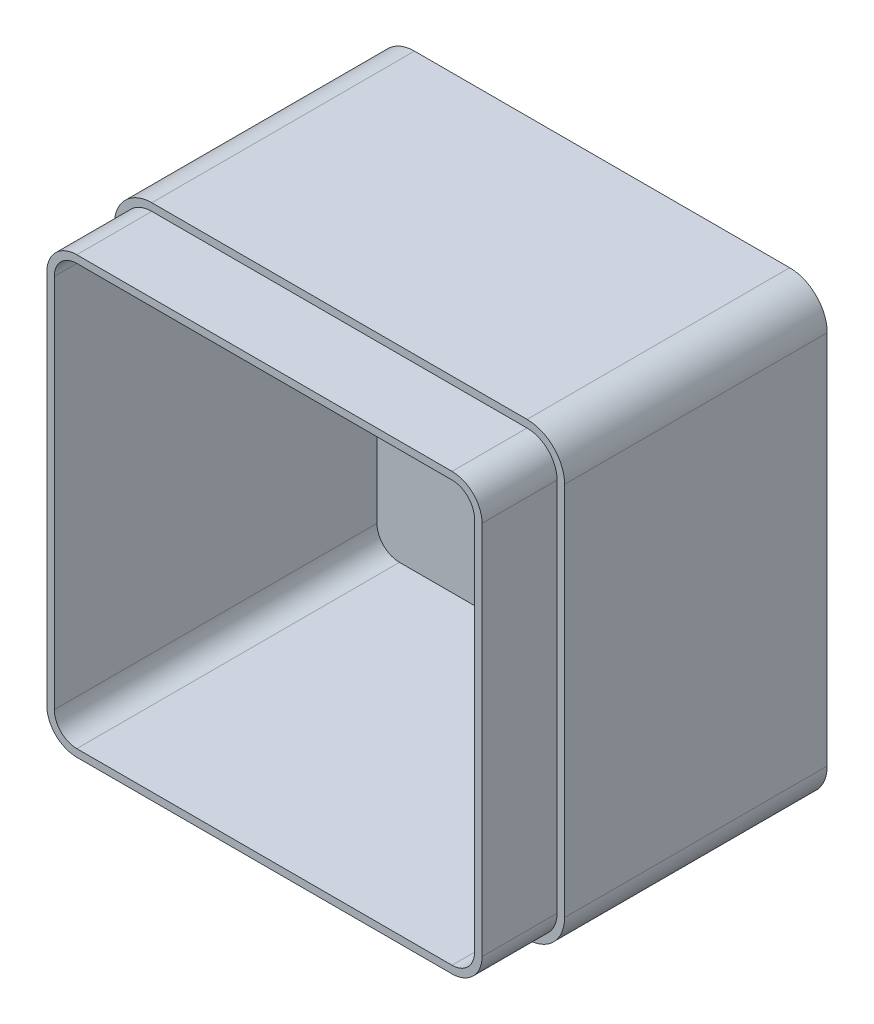
SolidWorks part; units mm, degrees
ref_plane "Front Plane" through (0, 0, 0) normal (0, 0, 1) x (1, 0, 0)
ref_plane "Top Plane" through (0, 0, 0) normal (0, 1, 0) x (1, 0, 0)
ref_plane "Right Plane" through (0, 0, 0) normal (1, 0, 0) x (0, 0, -1)
sketch "Sketch1" plane through (0, 0, 0) normal (0, 0, 1) x (1, 0, 0)
  line L1 (-60, -60) -> (60, -60)
  line L2 (-60, -60) -> (-60, 60)
  line L3 (-60, 60) -> (60, 60)
  line L4 (60, -60) -> (60, 60)
  line L5 (-60, -60) -> (60, 60) construction
  line L6 (-60, 60) -> (60, -60) construction
  point P0 (0, 0)
  dimension "D1" = 120
  dimension "D2" = 120
extrude "Boss-Extrude2" add sketch "Sketch1" along normal blind 70
fillet "Fillet1" radius 10 4 edges at (-60, -60, 35) (-60, 60, 35) (60, -60, 35) (60, 60, 35)
shell "Shell2" thickness 4
sketch "Sketch2" plane through (0, 0, 70) normal (0, 0, 1) x (1, 0, 0)
  line L0 (-58, 50) -> (-58, -50)
  line L1 (-50, -58) -> (50, -58)
  line L2 (58, -50) -> (58, 50)
  line L3 (50, 58) -> (-50, 58)
  line L4 (-60, 50) -> (-60, -50)
  line L5 (-50, -60) -> (50, -60)
  line L6 (60, -50) -> (60, 50)
  line L7 (50, 60) -> (-50, 60)
  line L8 (-60, 50) -> (-60, -50)
  line L9 (-50, -60) -> (50, -60)
  line L10 (60, -50) -> (60, 50)
  line L11 (50, 60) -> (-50, 60)
  arc A0 (-58, -50) -> (-50, -58) centre (-50, -50) ccw
  arc A1 (50, -58) -> (58, -50) centre (50, -50) ccw
  arc A2 (58, 50) -> (50, 58) centre (50, 50) ccw
  arc A3 (-50, 58) -> (-58, 50) centre (-50, 50) ccw
  arc A4 (-60, -50) -> (-50, -60) centre (-50, -50) ccw
  arc A5 (50, -60) -> (60, -50) centre (50, -50) ccw
  arc A6 (60, 50) -> (50, 60) centre (50, 50) ccw
  arc A7 (-50, 60) -> (-60, 50) centre (-50, 50) ccw
  arc A8 (-60, -50) -> (-50, -60) centre (-50, -50) ccw
  arc A9 (50, -60) -> (60, -50) centre (50, -50) ccw
  arc A10 (60, 50) -> (50, 60) centre (50, 50) ccw
  arc A11 (-50, 60) -> (-60, 50) centre (-50, 50) ccw
  dimension "D1" = 0
  dimension "D2" = 2
extrude "Boss-Extrude3" add sketch "Sketch2" along normal blind 20 contours L2 A2 L3 A3 L0 A0 L1 A1
sketch "Sketch4" plane through (0, 0, 90) normal (0, 0, 1) x (1, 0, 0)
  line L8 (56, -50) -> (56, 50)
  line L9 (50, 56) -> (-50, 56)
  line L10 (-56, 50) -> (-56, -50)
  line L11 (-50, -56) -> (50, -56)
  line L12 (56, -50) -> (56, 50)
  line L13 (50, 56) -> (-50, 56)
  line L14 (-56, 50) -> (-56, -50)
  line L15 (-50, -56) -> (50, -56)
  arc A8 (50, -56) -> (56, -50) centre (50, -50) ccw
  arc A9 (56, 50) -> (50, 56) centre (50, 50) ccw
  arc A10 (-50, 56) -> (-56, 50) centre (-50, 50) ccw
  arc A11 (-56, -50) -> (-50, -56) centre (-50, -50) ccw
  arc A12 (50, -56) -> (56, -50) centre (50, -50) ccw
  arc A13 (56, 50) -> (50, 56) centre (50, 50) ccw
  arc A14 (-50, 56) -> (-56, 50) centre (-50, 50) ccw
  arc A15 (-56, -50) -> (-50, -56) centre (-50, -50) ccw
  dimension "D1" = 2
extrude "Cut-Extrude3" cut sketch "Sketch4" against normal blind 20
